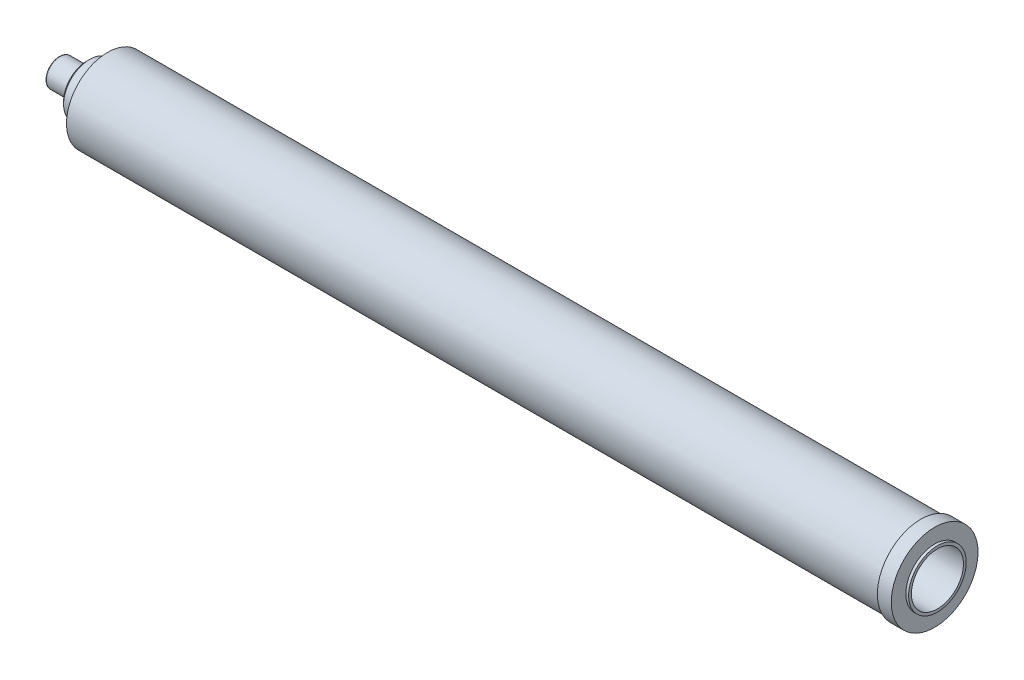
SolidWorks part; units mm, degrees
material "6061 Alloy"
ref_plane "Front Plane" through (0, 0, 0) normal (0, 0, 1) x (1, 0, 0)
ref_plane "Top Plane" through (0, 0, 0) normal (0, 1, 0) x (1, 0, 0)
ref_plane "Right Plane" through (0, 0, 0) normal (1, 0, 0) x (0, 0, -1)
sketch "Sketch1" plane through (0, 0, 0) normal (0, 0, 1) x (1, 0, 0)
  line L0 (0, 0) -> (0, 12.7)
  line L1 (0, 12.7) -> (25.4, 12.7)
  line L2 (25.4, 12.7) -> (25.4, 23.8125)
  line L3 (25.4, 23.8125) -> (44.45, 23.8125)
  line L4 (44.45, 23.8125) -> (44.45, 37.6555)
  line L5 (44.45, 37.6555) -> (788.416, 37.6555)
  line L6 (788.416, 37.6555) -> (788.416, 39.6875)
  line L7 (788.416, 39.6875) -> (801.116, 39.6875)
  line L8 (801.116, 39.6875) -> (801.116, 0)
  line L9 (801.116, 0) -> (0, 0)
  dimension "D1" = 25.4
  dimension "D2" = 23.8125
  dimension "D3" = 12.7
  dimension "D4" = 44.45
  dimension "D5" = 743.966
  dimension "D6" = 12.7
  dimension "D7" = 39.6875
  dimension "D8" = 37.6555
revolve "Revolve1" add sketch "Sketch1" angle 360 about L9
chamfer "Chamfer1" distance 2.54 angle 45 1 edges at (25.4, 23.8125, 0)
hole_wizard "CSK for 3/8 Flat Head Machine Screw (100)1" positions "Sketch3" profile "Sketch4" countersink size "3/8" standard "ANSI Inch"
sketch "Sketch3" plane through (0, 0, 0) normal (-1, 0, 0) x (0, 0, 1)
  point P0 (0, 0)
sketch "Sketch4" plane through (0, 0, 0) normal (0, 1, 0) x (0, 0, 1)
  line L0 (0, 0) -> (0, 28.4295)
  line L1 (0, 28.4295) -> (5.0419, 25.4)
  line L2 (5.0419, 25.4) -> (5.0419, 3.8896)
  line L3 (5.0419, 3.8896) -> (9.6774, 0)
  line L5 (9.6774, 0) -> (0, 0)
  line L6 (-5.0419, 3.8896) -> (-9.6774, 0) construction
  line L10 (0, 28.4295) -> (-5.0419, 25.4) construction
  line L11 (0, -6.35) -> (0, 107.95) construction
  dimension "Hole Dia." = 10.0838
  dimension "Hole Depth" = 25.4
  dimension "Near C'Sink Dia." = 19.3548
  dimension "Near C'Sink Angle" = 100
  dimension "Drill Angle" = 118
fillet "Fillet2" radius 1.27 1 edges at (0, 12.7, 0)
sketch "Sketch5" plane through (801.116, 0, 0) normal (1, 0, 0) x (0, 0, -1)
  circle A0 centre (0, 0) radius 23.8125
  circle A1 centre (0, 0) radius 26.3525
  dimension "D1" = 47.625
  dimension "D2" = 2.54
extrude "Boss-Extrude1" add sketch "Sketch5" along normal blind 2.54
sketch "Sketch6" plane through (803.656, 0, 0) normal (1, 0, 0) x (0, 0, -1)
  circle A0 centre (0, 0) radius 23.8125
extrude "Cut-Extrude1" cut sketch "Sketch6" against normal blind 508
